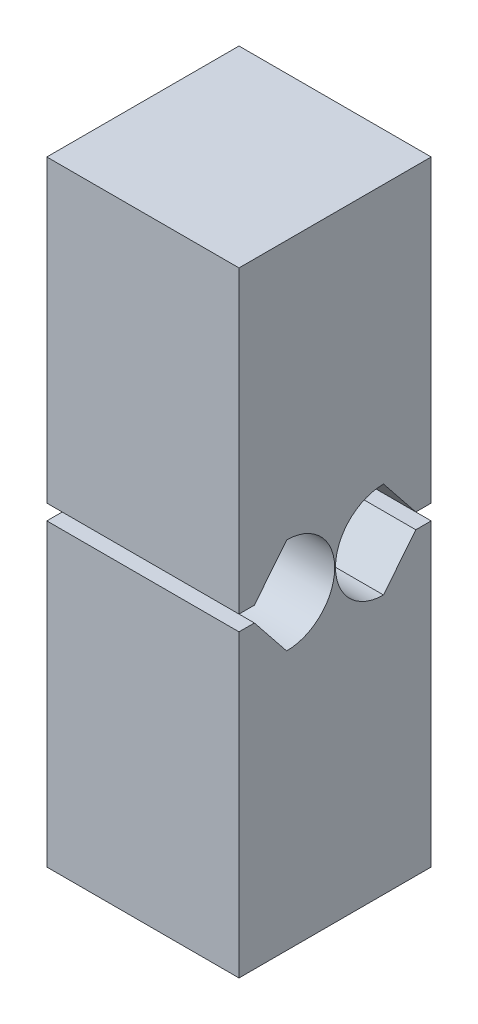
SolidWorks part; units mm, degrees
material "Beryllium Copper, UNS C17200"
ref_plane "Front Plane" through (0, 0, 0) normal (0, 0, 1) x (1, 0, 0)
ref_plane "Top Plane" through (0, 0, 0) normal (0, 1, 0) x (1, 0, 0)
ref_plane "Right Plane" through (0, 0, 0) normal (1, 0, 0) x (0, 0, -1)
sketch "Sketch1" plane through (0, 0, 0) normal (0, 1, 0) x (1, 0, 0)
  line L1 (-3.175, 3.175) -> (3.175, 3.175)
  line L2 (-3.175, 3.175) -> (-3.175, -3.175)
  line L3 (-3.175, -3.175) -> (3.175, -3.175)
  line L4 (3.175, 3.175) -> (3.175, -3.175)
  dimension "D1" = 3.175
  dimension "D2" = 3.175
  dimension "D3" = 3.175
  dimension "D4" = 3.175
extrude "Boss-Extrude1" add sketch "Sketch1" along normal mid plane 20.32
sketch "Sketch2" plane through (3.175, 0, 0) normal (1, 0, 0) x (0, 0, -1)
  line L0 (-3.175, 0.254) -> (-3.175, -0.254)
  line L1 (-3.175, 10.16) -> (-3.175, -10.16) construction
  line L2 (-3.175, -0.254) -> (-2.667, -0.254)
  line L3 (-2.667, -0.254) -> (-1.6002, -1.5875)
  line L4 (-3.175, 0.254) -> (-2.667, 0.254)
  line L5 (-2.667, 0.254) -> (-1.6002, 1.5875)
  arc A0 (-1.6002, 1.5875) -> (-1.6002, -1.5875) centre (-1.6002, 0) cw
  dimension "D1" = 0.254
  dimension "D2" = 0.254
  dimension "D3" = 0.508
  dimension "D4" = 0.508
extrude "Cut-Extrude1" cut sketch "Sketch2" against normal up to next
mirror "Mirror1" about plane through (0, 0, 0) normal (0, 0, 1) of "Cut-Extrude1"
sketch "Sketch3" [suppressed] plane through (-3.175, 0, 0) normal (-1, 0, 0) x (0, 0, 1)
  line L0 (-3.175, -10.16) -> (3.175, -10.16) construction
  point P0 (0, 0)
  dimension "D1" = 10.16
